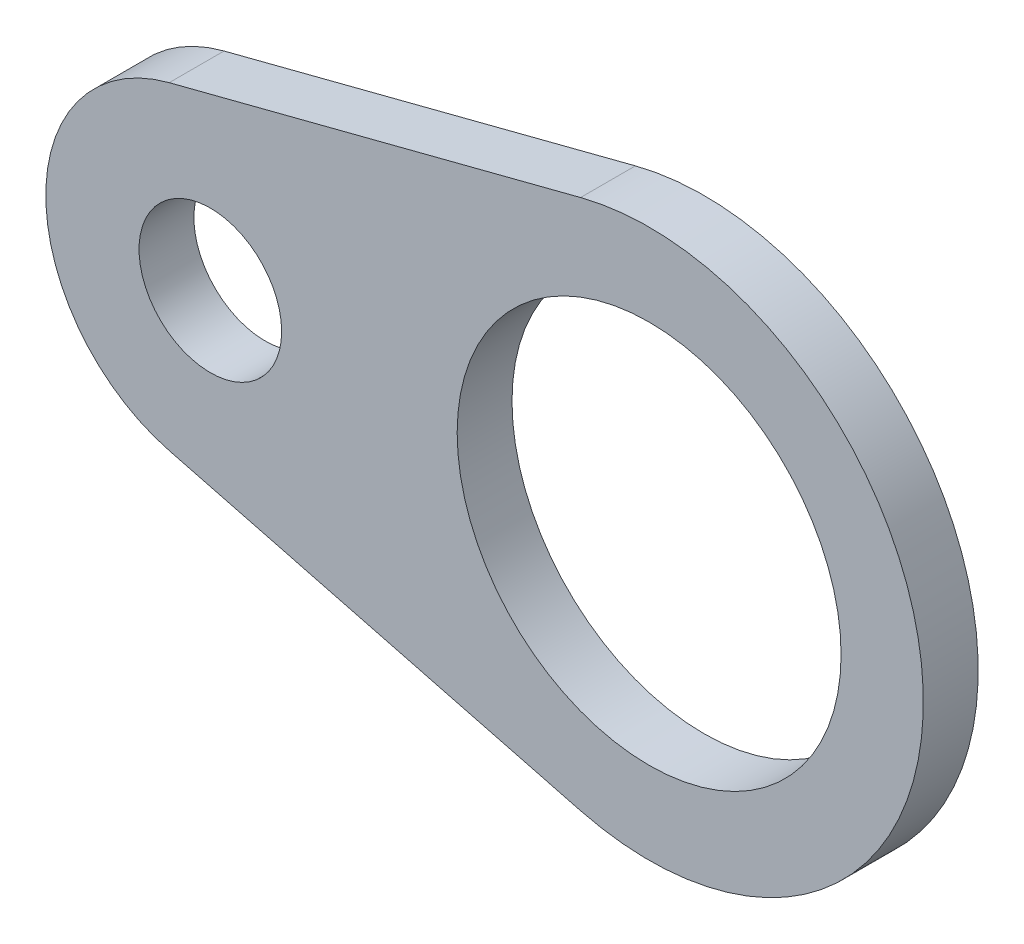
SolidWorks part; units mm, degrees
material "Q235"
ref_plane "前视基准面" through (0, 0, 0) normal (0, 0, 1) x (1, 0, 0)
ref_plane "上视基准面" through (0, 0, 0) normal (0, 1, 0) x (1, 0, 0)
ref_plane "右视基准面" through (0, 0, 0) normal (1, 0, 0) x (0, 0, -1)
sketch "草图1" plane through (0, 0, 0) normal (0, 0, 1) x (1, 0, 0)
  line L0 (0, 0) -> (-40, 0) construction
  line L1 (-43.75, 14.5237) -> (-6.25, 24.2061)
  line L2 (-43.75, -14.5237) -> (-6.25, -24.2061)
  circle A0 centre (0, 0) radius 17.5
  circle A1 centre (-40, 0) radius 6.5
  arc A2 (-43.75, 14.5237) -> (-43.75, -14.5237) centre (-40, 0) ccw
  arc A3 (-6.25, -24.2061) -> (-6.25, 24.2061) centre (0, 0) ccw
  dimension "D1" = 35
  dimension "D2" = 13
  dimension "D4" = 50
  dimension "D5" = 30
  dimension "D3" = 40
extrude "凸台-拉伸1" add sketch "草图1" along normal blind 5
